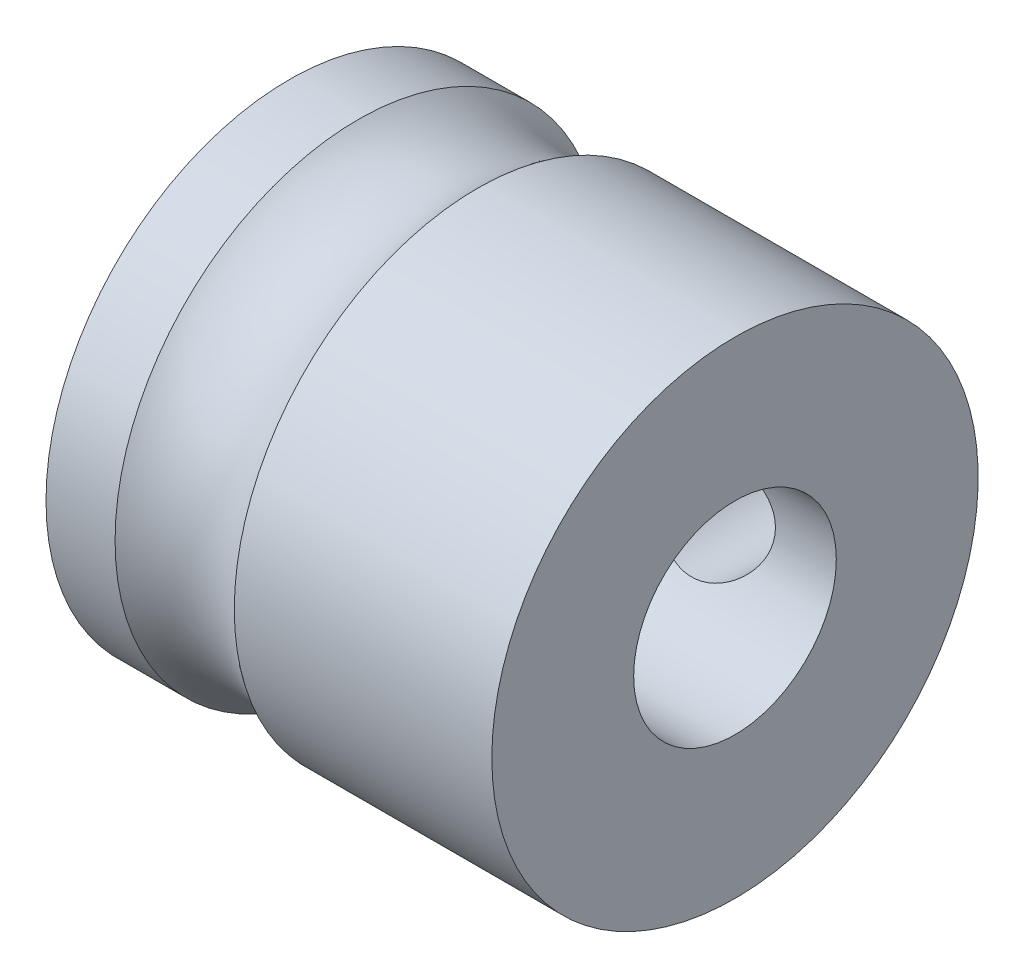
SolidWorks part; units mm, degrees
ref_plane "Front Plane" through (0, 0, 0) normal (0, 0, 1) x (1, 0, 0)
ref_plane "Top Plane" through (0, 0, 0) normal (0, 1, 0) x (1, 0, 0)
ref_plane "Right Plane" through (0, 0, 0) normal (1, 0, 0) x (0, 0, -1)
ref_plane "Plane1" through (0, 0, -4.4582) normal (0, 0, -1) x (-1, 0, 0)
sketch "Sketch1" plane through (0, 0, -4.4582) normal (0, 0, -1) x (-1, 0, 0)
  line L0 (-8.3272, -26.5544) -> (-8.3272, -32.5544)
  line L1 (-8.3272, -32.5544) -> (2.6728, -32.5544)
  line L2 (2.6728, -32.5544) -> (2.6728, -26.5544)
  line L3 (2.6728, -26.5544) -> (0.9685, -26.5544)
  line L4 (-1.9729, -26.5544) -> (-8.3272, -26.5544)
  line L5 (-8.3272, -32.5544) -> (2.6728, -32.5544) construction
  arc A0 (0.9685, -26.5544) -> (-1.9729, -26.5544) centre (-0.5022, -24.6414) cw
revolve "Revolve1" add sketch "Sketch1" angle 360 about L5
hole_wizard "Ø5.0 (5) Diameter Hole1" positions "Sketch3" profile "Sketch2" hole size "Ø5.0" standard "ANSI Metric"
sketch "Sketch3" plane through (-2.6728, 0, 0) normal (-1, 0, 0) x (0, 0, 1)
  point P0 (-4.4582, -32.5544)
sketch "Sketch2" plane through (-2.6728, -32.5544, -4.4582) normal (0, 1, 0) x (0, 0, 1)
  line L0 (0, 0) -> (0, 11)
  line L1 (0, 11) -> (2.5, 11)
  line L2 (2.5, 11) -> (2.5, 0)
  line L5 (2.5, 0) -> (0, 0)
  line L11 (0, -6.35) -> (0, 107.95) construction
  dimension "Thru Hole Dia." = 5
  dimension "Thru Hole Depth" = 11
hole_wizard "Ø3.0 (3) Diameter Hole1" positions "3DSketch1" profile "Sketch4" hole size "Ø3.0" standard "ANSI Metric"
sketch3d "3DSketch1"
  point P0 (5.3272, -32.8364, -10.4516)
sketch "Sketch4" plane through (5.3272, -32.8364, -10.4516) normal (1, 0, 0) x (0, 0.9989, -0.047)
  line L0 (0, 0) -> (0, 3.5)
  line L1 (0, 3.5) -> (1.5, 3.5)
  line L2 (1.5, 3.5) -> (1.5, 0)
  line L5 (1.5, 0) -> (0, 0)
  line L11 (0, -6.35) -> (0, 107.95) construction
  dimension "Thru Hole Dia." = 3
  dimension "Thru Hole Depth" = 3.5
ref_plane "Plane2" through (-0.9685, 0, 0) normal (1, 0, 0) x (0, 0, -1)
ref_plane "Plane3" through (1.9729, 0, 0) normal (1, 0, 0) x (0, 0, -1)
ref_plane "Plane4" through (0.5022, 0, 0) normal (1, 0, 0) x (0, 0, -1)
sketch "Sketch5" plane through (0.5022, 0, 0) normal (1, 0, 0) x (0, 0, -1)
  point P0 (4.4582, -32.5544)
ref_point "Point1"
